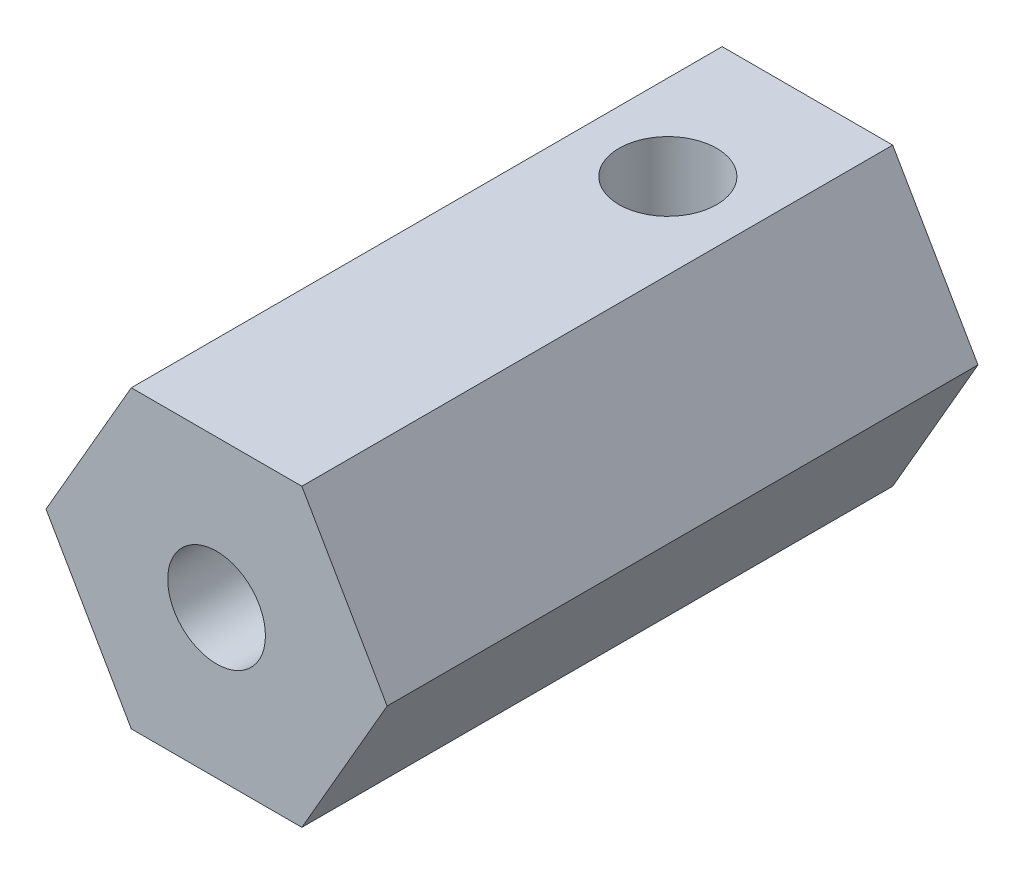
SolidWorks part; units mm, degrees
material "6061-T6 (SS)"
ref_plane "Front" through (0, 0, 0) normal (0, 0, 1) x (1, 0, 0)
ref_plane "Top" through (0, 0, 0) normal (0, 1, 0) x (1, 0, 0)
ref_plane "Right" through (0, 0, 0) normal (1, 0, 0) x (0, 0, -1)
sketch "Sketch1" plane through (0, 0, 0) normal (0, 0, 1) x (1, 0, 0)
  line L1 (7.3323, 0) -> (3.6662, 6.35)
  line L2 (3.6662, 6.35) -> (-3.6662, 6.35)
  line L3 (-3.6662, 6.35) -> (-7.3323, 0)
  line L4 (-7.3323, 0) -> (-3.6662, -6.35)
  line L5 (-3.6662, -6.35) -> (3.6662, -6.35)
  line L6 (3.6662, -6.35) -> (7.3323, 0)
  circle A0 centre (0, 0) radius 6.35 construction
  dimension "D1" = 12.7
extrude "Boss-Extrude1" add sketch "Sketch1" along normal blind 25.4
sketch "Sketch2" plane through (0, 0, 0) normal (0, 0, -1) x (-1, 0, 0)
  circle A0 centre (0, 0) radius 3
  dimension "D1" = 6
extrude "Cut-Extrude1" cut sketch "Sketch2" against normal blind 12.7
sketch "Sketch5" plane through (0, 0, 25.4) normal (0, 0, 1) x (1, 0, 0)
  line L0 (0, 6.35) -> (0, 0) construction
  line L1 (3.6662, 6.35) -> (-3.6662, 6.35) construction
hole_wizard "Tap Drill for M5x0.8 Tap1" positions "3DSketch3" profile "Sketch6" hole size "M5x0.8" standard "ANSI Metric" end condition up to next
sketch3d "3DSketch3"
  point P0 (0, 0, 25.4)
sketch "Sketch6" plane through (0, 0, 25.4) normal (1, 0, 0) x (0, -1, 0)
  line L0 (0, 0) -> (0, 12.7)
  line L1 (0, 12.7) -> (2.1, 12.7)
  line L2 (2.1, 12.7) -> (2.1, 0)
  line L5 (2.1, 0) -> (0, 0)
  line L11 (0, -6.35) -> (0, 107.95) construction
  dimension "Thru Hole Dia." = 4.2
  dimension "Thru Hole Depth" = 12.7
sketch "Sketch7" plane through (0, 6.35, 0) normal (0, 1, 0) x (1, 0, 0)
  line L0 (0, 0) -> (0, -6) construction
  line L1 (3.6662, 0) -> (-3.6662, 0) construction
  dimension "D1" = 6
hole_wizard "Tap Drill for M5x0.8 Tap2" positions "3DSketch4" profile "Sketch8" hole size "M5x0.8" standard "ANSI Metric"
sketch3d "3DSketch4"
  point P0 (0, 6.35, 6)
sketch "Sketch8" plane through (0, 6.35, 6) normal (1, 0, 0) x (0, 0, 1)
  line L0 (0, 0) -> (0, 3.35)
  line L1 (0, 3.35) -> (2.1, 3.35)
  line L2 (2.1, 3.35) -> (2.1, 0)
  line L5 (2.1, 0) -> (0, 0)
  line L11 (0, -6.35) -> (0, 107.95) construction
  dimension "Thru Hole Dia." = 4.2
  dimension "Thru Hole Depth" = 3.35
